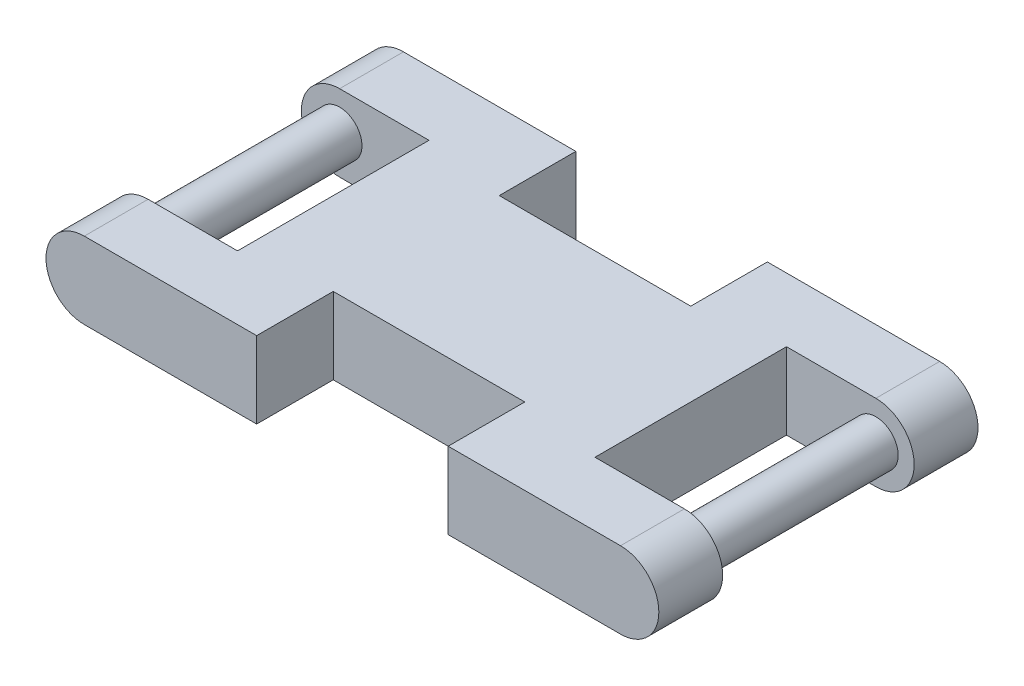
SolidWorks part; units mm, degrees
ref_plane "Front Plane" through (0, 0, 0) normal (0, 0, 1) x (1, 0, 0)
ref_plane "Top Plane" through (0, 0, 0) normal (0, 1, 0) x (1, 0, 0)
ref_plane "Right Plane" through (0, 0, 0) normal (1, 0, 0) x (0, 0, -1)
sketch "Sketch1" plane through (0, 0, 0) normal (0, 0, 1) x (1, 0, 0)
  line L0 (-105, 0) -> (105, 0) construction
  line L1 (-105, 15) -> (105, 15)
  line L2 (-105, -15) -> (105, -15)
  arc A0 (-105, 15) -> (-105, -15) centre (-105, 0) ccw
  arc A1 (105, -15) -> (105, 15) centre (105, 0) ccw
  point P2 (0, 0)
  dimension "D2" = 15
  dimension "D1" = 210
extrude "Boss-Extrude1" add sketch "Sketch1" along normal blind 125
sketch "Sketch2" plane through (0, 15, 0) normal (0, 1, 0) x (1, 0, 0)
  line L1 (-70, -25) -> (-120, -25)
  line L2 (-70, -25) -> (-70, -100)
  line L3 (-70, -100) -> (-120, -100)
  line L4 (-120, -25) -> (-120, -100)
  line L5 (-120, 0) -> (-120, -125) construction
  line L6 (105, -125) -> (105, 0) construction
  line L7 (0, 0) -> (0, -42.2744)
  line L8 (105, 0) -> (-105, 0) construction
  line L9 (120, -25) -> (120, -100)
  line L10 (70, -100) -> (120, -100)
  line L11 (70, -25) -> (70, -100)
  line L12 (70, -25) -> (120, -25)
  point P10 (105, -62.5)
  point P11 (-70, -62.5)
  line M3 (-105, 0) -> (-105, -125)
  line M5 (105, -125) -> (105, 0)
  dimension "D1" = 75
  dimension "D2" = 50
extrude "Cut-Extrude1" cut sketch "Sketch2" against normal blind 100 contours L3 L2 L1 M3 | L1 L4 L3 M3 | L12 L10 L9 M5 | L12 L11 L10 M5
sketch "Sketch3" plane through (0, 0, 25) normal (0, 0, 1) x (1, 0, 0)
  line L0 (0, 15) -> (0, 0)
  line L1 (105, 15) -> (-105, 15) construction
  circle A0 centre (-105, 0) radius 8.75
  circle A1 centre (105, 0) radius 8.75
  dimension "D1" = 17.5
extrude "Boss-Extrude2" add sketch "Sketch3" along normal up to surface (75 mm away) contours A0 | A1 up to face at (-91.25, 0, 100)
sketch "Sketch4" plane through (0, 15, 0) normal (0, 1, 0) x (1, 0, 0)
  line L0 (105, -125) -> (-105, -125) construction
  line L1 (-37.5, -125) -> (37.5, -125)
  line L2 (-37.5, -125) -> (-37.5, -95)
  line L3 (-37.5, -95) -> (37.5, -95)
  line L4 (37.5, -125) -> (37.5, -95)
  line L5 (70, -62.5) -> (104.7907, -62.5)
  line L6 (70, -25) -> (70, -100) construction
  line L7 (37.5, 0) -> (37.5, -30)
  line L8 (-37.5, -30) -> (37.5, -30)
  line L9 (-37.5, 0) -> (-37.5, -30)
  line L10 (-37.5, 0) -> (37.5, 0)
  point P14 (0, -125)
  line M12 (-105, -125) -> (105, -125)
  line M18 (105, 0) -> (-105, 0)
  dimension "D1" = 75
  dimension "D2" = 30
extrude "Cut-Extrude2" cut sketch "Sketch4" against normal through all contours L9 L8 L7 M18 | L4 L3 L2 M12
